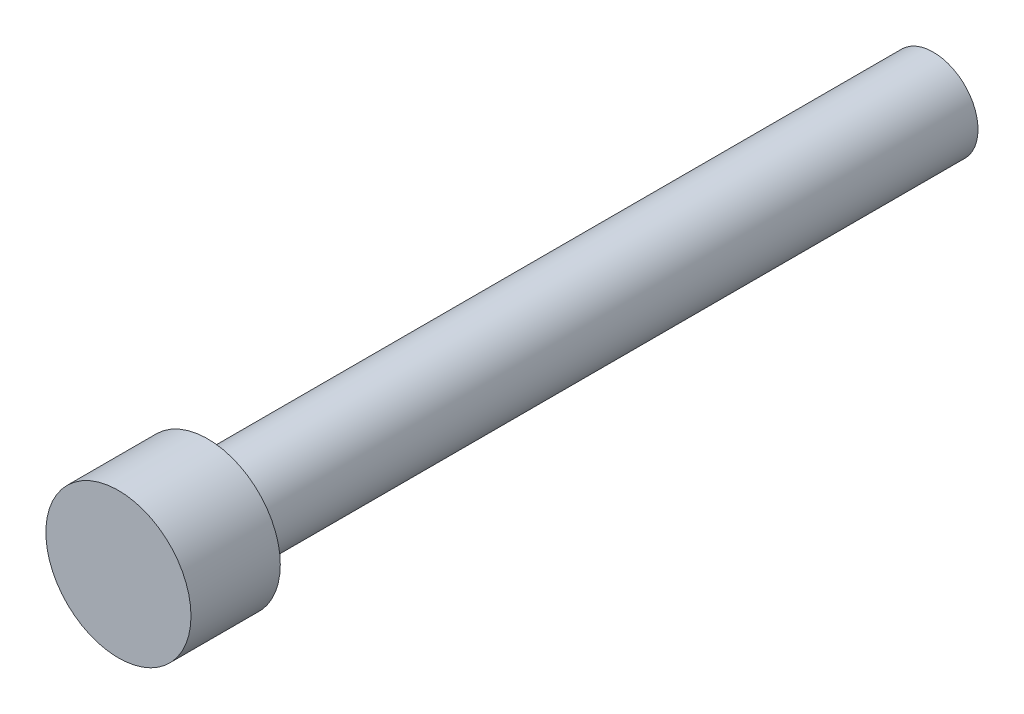
SolidWorks part; units mm, degrees
ref_plane "前视基准面" through (0, 0, 0) normal (0, 0, 1) x (1, 0, 0)
ref_plane "上视基准面" through (0, 0, 0) normal (0, 1, 0) x (1, 0, 0)
ref_plane "右视基准面" through (0, 0, 0) normal (1, 0, 0) x (0, 0, -1)
other "Configuration Table"
sketch "草图1" plane through (0, 0, 0) normal (0, 0, 1) x (1, 0, 0)
  circle A0 centre (0, 0) radius 4
extrude "Shank_simplified" add sketch "草图1" along normal blind 65
sketch "草图2" plane through (0, 0, 65) normal (0, 0, 1) x (1, 0, 0)
  circle A0 centre (0, 0) radius 6.5
extrude "Purchased_head_simplified" add sketch "草图2" along normal blind 8
